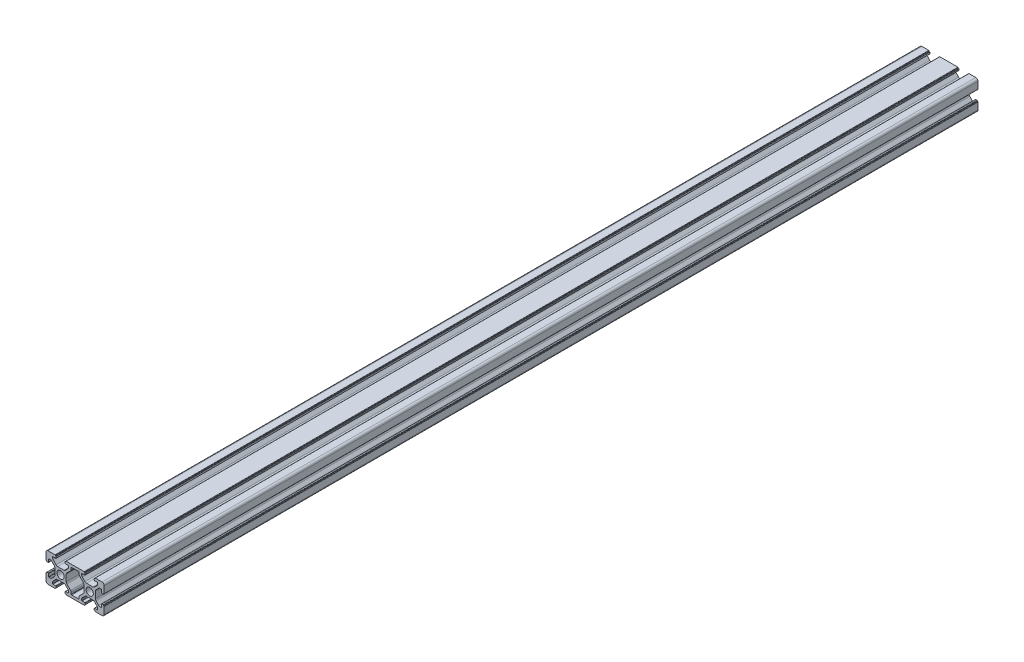
SolidWorks part; units mm, degrees
material "6063-O"
ref_plane "Front Plane" through (0, 0, 0) normal (0, 0, 1) x (1, 0, 0)
ref_plane "Top Plane" through (0, 0, 0) normal (0, 1, 0) x (1, 0, 0)
ref_plane "Right Plane" through (0, 0, 0) normal (1, 0, 0) x (0, 0, -1)
sketch "Sketch1" plane through (0, 0, 0) normal (0, 0, 1) x (1, 0, 0)
  line L0 (1.5, 0) -> (6.2, 0)
  line L1 (40, 1.5) -> (40, 6.2)
  line L2 (38.5, 20) -> (33.8, 20)
  line L3 (0, 18.5) -> (0, 13.8)
  line L4 (17.6, 1.8) -> (22.4, 1.8)
  line L5 (32.218, 13.9) -> (27.782, 13.9)
  line L6 (26.1, 12.218) -> (26.1, 7.782)
  line L7 (17.6, 18.2) -> (22.4, 18.2)
  line L8 (12.218, 13.9) -> (7.9864, 13.9)
  line L9 (6.1, 12.218) -> (6.1, 7.782)
  line L10 (7.782, 6.1) -> (12.218, 6.1)
  line L11 (13.9, 7.782) -> (13.9, 12.218)
  line L12 (27.782, 6.1) -> (32.218, 6.1)
  line L13 (33.9, 7.782) -> (33.9, 12.218)
  line L14 (26.7213, 14.3393) -> (24.9393, 16.1213)
  line L15 (33.2787, 14.3393) -> (35.0607, 16.1213)
  line L16 (34.3393, 13.2787) -> (36.1213, 15.0607)
  line L17 (25.6607, 6.7213) -> (23.1393, 4.2)
  line L18 (15.2, 1.8) -> (13.4, 1.8)
  line L19 (26.7213, 5.6607) -> (24.9393, 3.8787)
  line L20 (24.8, 1.8) -> (26.6, 1.8)
  line L21 (15.3, 18.2) -> (13.1, 18.2)
  line L22 (13.2787, 14.3393) -> (15.1607, 16.2213)
  line L23 (14.3393, 13.2787) -> (16.8607, 15.8)
  line L24 (5.6607, 6.7213) -> (3.8787, 4.9393)
  line L25 (6.7213, 5.6607) -> (4.9393, 3.8787)
  line L26 (6.897, 14.3689) -> (4.9106, 16.4674)
  line L27 (5.6607, 13.2787) -> (3.8787, 15.0607)
  line L28 (14.3393, 6.7213) -> (16.8607, 4.2)
  line L29 (13.2787, 5.6607) -> (15.0607, 3.8787)
  line L30 (24.8, 18.2) -> (26.6, 18.2)
  line L31 (25.6607, 13.2787) -> (23.1393, 15.8)
  line L32 (34.3393, 6.7213) -> (36.1213, 4.9393)
  line L33 (33.2787, 5.6607) -> (35.0607, 3.8787)
  line L34 (1.8, 15.2) -> (1.8, 13.4)
  line L35 (24.5, 2.1) -> (24.5, 2.818)
  line L36 (4.5, 2.1) -> (4.5, 2.818)
  line L37 (2.818, 4.5) -> (2.1, 4.5)
  line L38 (4.5, 17.9) -> (4.5, 17.4986)
  line L39 (2.818, 15.5) -> (2.1, 15.5)
  line L40 (15.6, 17.9) -> (15.6, 17.282)
  line L41 (15.5, 2.818) -> (15.5, 2.1)
  line L42 (38.2, 15.2) -> (38.2, 13.4)
  line L43 (35.5, 2.818) -> (35.5, 2.1)
  line L44 (37.182, 4.5) -> (37.9, 4.5)
  line L45 (35.5, 17.182) -> (35.5, 17.9)
  line L46 (37.182, 15.5) -> (37.9, 15.5)
  line L47 (17.3, 2.1) -> (17.3, 3.1393)
  line L48 (22.7, 2.1) -> (22.7, 3.1393)
  line L49 (17.3, 17.9) -> (17.3, 16.8607)
  line L50 (22.7, 17.9) -> (22.7, 16.8607)
  line L51 (24.5, 17.9) -> (24.5, 17.182)
  line L52 (6.9, 19.3) -> (6.9, 18.2)
  line L53 (13.1, 19.3) -> (13.1, 18.2)
  line L54 (6.9, 1.5) -> (6.9, 0.7)
  line L55 (13.1, 1.5) -> (13.1, 0.7)
  line L56 (13.8, 0) -> (26.2, 0)
  line L57 (6.6, 1.8) -> (4.8, 1.8)
  line L58 (6.9, 18.2) -> (4.8, 18.2)
  line L59 (6.2, 20) -> (1.5, 20)
  line L60 (39.3, 6.9) -> (38.5, 6.9)
  line L61 (39.3, 13.1) -> (38.5, 13.1)
  line L62 (1.5, 13.1) -> (0.7, 13.1)
  line L63 (1.5, 6.9) -> (0.7, 6.9)
  line L64 (0, 6.2) -> (0, 1.5)
  line L65 (1.8, 6.6) -> (1.8, 4.8)
  line L66 (38.2, 6.6) -> (38.2, 4.8)
  line L67 (40, 13.8) -> (40, 18.5)
  line L68 (33.1, 19.3) -> (33.1, 18.5)
  line L69 (26.9, 19.3) -> (26.9, 18.5)
  line L70 (26.9, 1.5) -> (26.9, 0.7)
  line L71 (33.1, 1.5) -> (33.1, 0.7)
  line L72 (33.8, 0) -> (38.5, 0)
  line L73 (33.4, 1.8) -> (35.2, 1.8)
  line L74 (26.2, 20) -> (13.8, 20)
  line L75 (33.4, 18.2) -> (35.2, 18.2)
  line L76 (6.7, 0.5) -> (6.6, 0.5)
  line L77 (6.4, 0.3) -> (6.4, 0.2)
  line L78 (13.3, 0.5) -> (13.4, 0.5)
  line L79 (13.6, 0.3) -> (13.6, 0.2)
  line L80 (26.7, 0.5) -> (26.6, 0.5)
  line L81 (26.4, 0.3) -> (26.4, 0.2)
  line L82 (33.3, 0.5) -> (33.4, 0.5)
  line L83 (33.6, 0.3) -> (33.6, 0.2)
  line L85 (6.4, 19.8) -> (6.4, 19.7)
  line L86 (6.6, 19.5) -> (6.7, 19.5)
  line L87 (13.6, 19.8) -> (13.6, 19.7)
  line L88 (13.4, 19.5) -> (13.3, 19.5)
  line L89 (26.4, 19.8) -> (26.4, 19.7)
  line L90 (26.6, 19.5) -> (26.7, 19.5)
  line L91 (33.6, 19.8) -> (33.6, 19.7)
  line L92 (33.4, 19.5) -> (33.3, 19.5)
  line L93 (0.5, 13.3) -> (0.5, 13.4)
  line L94 (0.3, 13.6) -> (0.2, 13.6)
  line L95 (0.5, 6.7) -> (0.5, 6.6)
  line L96 (0.3, 6.4) -> (0.2, 6.4)
  line L97 (39.5, 13.3) -> (39.5, 13.4)
  line L98 (39.7, 13.6) -> (39.8, 13.6)
  line L99 (39.5, 6.7) -> (39.5, 6.6)
  line L100 (39.7, 6.4) -> (39.8, 6.4)
  circle A0 centre (10, 10) radius 2.5
  circle A1 centre (30, 10) radius 2.5
  arc A2 (38.5, 0) -> (40, 1.5) centre (38.5, 1.5) ccw
  arc A3 (40, 18.5) -> (38.5, 20) centre (38.5, 18.5) ccw
  arc A4 (1.5, 0) -> (0, 1.5) centre (1.5, 1.5) cw
  arc A5 (1.5, 20) -> (0, 18.5) centre (1.5, 18.5) ccw
  arc A6 (26.7213, 5.6607) -> (27.782, 6.1) centre (27.782, 4.6) cw
  arc A7 (32.218, 6.1) -> (33.2787, 5.6607) centre (32.218, 4.6) cw
  arc A8 (33.9, 7.782) -> (34.3393, 6.7213) centre (35.4, 7.782) ccw
  arc A9 (33.2787, 14.3393) -> (32.218, 13.9) centre (32.218, 15.4) cw
  arc A10 (14.3393, 6.7213) -> (13.9, 7.782) centre (15.4, 7.782) cw
  arc A11 (14.3393, 13.2787) -> (13.9, 12.218) centre (15.4, 12.218) ccw
  arc A12 (25.6607, 6.7213) -> (26.1, 7.782) centre (24.6, 7.782) ccw
  arc A13 (26.1, 12.218) -> (25.6607, 13.2787) centre (24.6, 12.218) ccw
  arc A14 (27.782, 13.9) -> (26.7213, 14.3393) centre (27.782, 15.4) cw
  arc A15 (5.6607, 13.2787) -> (6.1, 12.218) centre (4.6, 12.218) cw
  arc A16 (5.6607, 6.7213) -> (6.1, 7.782) centre (4.6, 7.782) ccw
  arc A17 (13.2787, 5.6607) -> (12.218, 6.1) centre (12.218, 4.6) ccw
  arc A18 (6.7213, 5.6607) -> (7.782, 6.1) centre (7.782, 4.6) cw
  arc A19 (13.2787, 14.3393) -> (12.218, 13.9) centre (12.218, 15.4) cw
  arc A20 (6.897, 14.3689) -> (7.9864, 13.9) centre (7.9864, 15.4) ccw
  arc A21 (36.1213, 4.9393) -> (37.182, 4.5) centre (37.182, 6) ccw
  arc A22 (36.1213, 15.0607) -> (37.182, 15.5) centre (37.182, 14) cw
  arc A23 (35.0607, 16.1213) -> (35.5, 17.182) centre (34, 17.182) ccw
  arc A24 (24.5, 17.182) -> (24.9393, 16.1213) centre (26, 17.182) ccw
  arc A25 (22.7, 16.8607) -> (23.1393, 15.8) centre (24.2, 16.8607) ccw
  arc A26 (17.3, 16.8607) -> (16.8607, 15.8) centre (15.8, 16.8607) cw
  arc A27 (4.9106, 16.4674) -> (4.5, 17.4986) centre (6, 17.4986) cw
  arc A28 (15.6, 17.282) -> (15.1607, 16.2213) centre (14.1, 17.282) cw
  arc A29 (3.8787, 15.0607) -> (2.818, 15.5) centre (2.818, 14) ccw
  arc A30 (3.8787, 4.9393) -> (2.818, 4.5) centre (2.818, 6) cw
  arc A31 (4.9393, 3.8787) -> (4.5, 2.818) centre (6, 2.818) ccw
  arc A32 (35.0607, 3.8787) -> (35.5, 2.818) centre (34, 2.818) cw
  arc A33 (24.9393, 3.8787) -> (24.5, 2.818) centre (26, 2.818) ccw
  arc A34 (22.7, 3.1393) -> (23.1393, 4.2) centre (24.2, 3.1393) cw
  arc A35 (17.3, 3.1393) -> (16.8607, 4.2) centre (15.8, 3.1393) ccw
  arc A36 (15.5, 2.818) -> (15.0607, 3.8787) centre (14, 2.818) ccw
  arc A37 (1.8, 6.6) -> (1.5, 6.9) centre (1.5, 6.6) ccw
  arc A38 (1.8, 13.4) -> (1.5, 13.1) centre (1.5, 13.4) cw
  arc A39 (17.6, 18.2) -> (17.3, 17.9) centre (17.6, 17.9) ccw
  arc A40 (22.4, 1.8) -> (22.7, 2.1) centre (22.4, 2.1) ccw
  arc A41 (17.6, 1.8) -> (17.3, 2.1) centre (17.6, 2.1) cw
  arc A42 (15.2, 1.8) -> (15.5, 2.1) centre (15.2, 2.1) ccw
  arc A43 (6.6, 1.8) -> (6.9, 1.5) centre (6.6, 1.5) cw
  arc A44 (13.4, 1.8) -> (13.1, 1.5) centre (13.4, 1.5) ccw
  arc A45 (24.8, 1.8) -> (24.5, 2.1) centre (24.8, 2.1) cw
  arc A46 (35.2, 1.8) -> (35.5, 2.1) centre (35.2, 2.1) ccw
  arc A47 (26.6, 1.8) -> (26.9, 1.5) centre (26.6, 1.5) cw
  arc A48 (33.4, 1.8) -> (33.1, 1.5) centre (33.4, 1.5) ccw
  arc A49 (26.9, 18.5) -> (26.6, 18.2) centre (26.6, 18.5) cw
  arc A50 (33.1, 18.5) -> (33.4, 18.2) centre (33.4, 18.5) ccw
  arc A51 (37.9, 4.5) -> (38.2, 4.8) centre (37.9, 4.8) ccw
  arc A52 (38.5, 13.1) -> (38.2, 13.4) centre (38.5, 13.4) cw
  arc A53 (38.5, 6.9) -> (38.2, 6.6) centre (38.5, 6.6) ccw
  arc A54 (38.2, 15.2) -> (37.9, 15.5) centre (37.9, 15.2) ccw
  arc A55 (35.2, 18.2) -> (35.5, 17.9) centre (35.2, 17.9) cw
  arc A56 (24.8, 18.2) -> (24.5, 17.9) centre (24.8, 17.9) ccw
  arc A57 (22.4, 18.2) -> (22.7, 17.9) centre (22.4, 17.9) cw
  arc A58 (15.3, 18.2) -> (15.6, 17.9) centre (15.3, 17.9) cw
  arc A59 (4.5, 17.9) -> (4.8, 18.2) centre (4.8, 17.9) cw
  arc A60 (1.8, 15.2) -> (2.1, 15.5) centre (2.1, 15.2) cw
  arc A61 (1.8, 4.8) -> (2.1, 4.5) centre (2.1, 4.8) ccw
  arc A62 (4.5, 2.1) -> (4.8, 1.8) centre (4.8, 2.1) ccw
  arc A63 (34.3393, 13.2787) -> (33.9, 12.218) centre (35.4, 12.218) ccw
  arc A64 (6.4, 0.2) -> (6.2, 0) centre (6.2, 0.2) cw
  arc A65 (6.6, 0.5) -> (6.4, 0.3) centre (6.6, 0.3) ccw
  arc A66 (6.7, 0.5) -> (6.9, 0.7) centre (6.7, 0.7) ccw
  arc A67 (13.6, 0.2) -> (13.8, 0) centre (13.8, 0.2) ccw
  arc A68 (13.4, 0.5) -> (13.6, 0.3) centre (13.4, 0.3) cw
  arc A69 (13.3, 0.5) -> (13.1, 0.7) centre (13.3, 0.7) cw
  arc A70 (26.4, 0.2) -> (26.2, 0) centre (26.2, 0.2) cw
  arc A71 (26.6, 0.5) -> (26.4, 0.3) centre (26.6, 0.3) ccw
  arc A72 (26.7, 0.5) -> (26.9, 0.7) centre (26.7, 0.7) ccw
  arc A73 (33.6, 0.2) -> (33.8, 0) centre (33.8, 0.2) ccw
  arc A74 (33.4, 0.5) -> (33.6, 0.3) centre (33.4, 0.3) cw
  arc A75 (33.3, 0.5) -> (33.1, 0.7) centre (33.3, 0.7) cw
  arc A76 (39.8, 6.4) -> (40, 6.2) centre (39.8, 6.2) cw
  arc A77 (39.5, 6.6) -> (39.7, 6.4) centre (39.7, 6.6) ccw
  arc A78 (39.5, 6.7) -> (39.3, 6.9) centre (39.3, 6.7) ccw
  arc A79 (39.5, 13.3) -> (39.3, 13.1) centre (39.3, 13.3) cw
  arc A80 (39.5, 13.4) -> (39.7, 13.6) centre (39.7, 13.4) cw
  arc A81 (39.8, 13.6) -> (40, 13.8) centre (39.8, 13.8) ccw
  arc A82 (33.3, 19.5) -> (33.1, 19.3) centre (33.3, 19.3) ccw
  arc A83 (33.6, 19.7) -> (33.4, 19.5) centre (33.4, 19.7) cw
  arc A84 (33.6, 19.8) -> (33.8, 20) centre (33.8, 19.8) cw
  arc A85 (26.7, 19.5) -> (26.9, 19.3) centre (26.7, 19.3) cw
  arc A86 (26.4, 19.7) -> (26.6, 19.5) centre (26.6, 19.7) ccw
  arc A87 (26.4, 19.8) -> (26.2, 20) centre (26.2, 19.8) ccw
  arc A88 (0.2, 6.4) -> (0, 6.2) centre (0.2, 6.2) ccw
  arc A89 (0.5, 6.6) -> (0.3, 6.4) centre (0.3, 6.6) cw
  arc A90 (0.5, 6.7) -> (0.7, 6.9) centre (0.7, 6.7) cw
  arc A91 (13.3, 19.5) -> (13.1, 19.3) centre (13.3, 19.3) ccw
  arc A92 (13.6, 19.7) -> (13.4, 19.5) centre (13.4, 19.7) cw
  arc A93 (13.6, 19.8) -> (13.8, 20) centre (13.8, 19.8) cw
  arc A94 (6.2, 20) -> (6.4, 19.8) centre (6.2, 19.8) cw
  arc A95 (6.7, 19.5) -> (6.9, 19.3) centre (6.7, 19.3) cw
  arc A96 (6.4, 19.7) -> (6.6, 19.5) centre (6.6, 19.7) ccw
  arc A97 (0.5, 13.3) -> (0.7, 13.1) centre (0.7, 13.3) ccw
  arc A98 (0.2, 13.6) -> (0, 13.8) centre (0.2, 13.8) cw
  arc A99 (0.5, 13.4) -> (0.3, 13.6) centre (0.3, 13.4) ccw
  point P87 (0, 0)
  point P178 (1.8, 6.9)
  point P181 (1.8, 13.1)
  point P186 (22.7, 1.8)
  point P193 (6.9, 1.8)
  point P204 (33.1, 1.8)
  point P209 (33.1, 18.2)
  point P216 (38.2, 6.9)
  point P243 (6.9, 0.5)
  point P248 (13.6, 0.5)
  point P257 (26.9, 0.5)
extrude "Boss-Extrude2" add sketch "Sketch1" along normal blind 600 contours A57 L7 A39 L49 A26 L23 A11 L11 A10 L28 A35 L47 A41 L4 A40 L48 A34 L17 A12 L6 A13 L31 A25 L50 | A0 | A1 | L59 A5 L3 A98 L94 A99 L93 A97 L62 A38 L34 A60 L39 A29 L27 A15 L9 A16 L24 A30 L37 A61 L65 A37 L63 A90 L95 A89 L96 A88 L64 A4 L0 A64 L77 A65 L76 A66 L54 A43 L57 A62 L36 A31 L25 A18 L10 A17 L29 A36 L41 A42 L18 A44 L55 A69 L78 A68 L79 A67 L56 A70 L81 A71 L80 A72 L70 A47 L20 A45 L35 A33 L19 A6 L12 A7 L33 A32 L43 A46 L73 A48 L71 A75 L82 A74 L83 A73 L72 A2 L1 A76 L100 A77 L99 A78 L60 A53 L66 A51 L44 A21 L32 A8 L13 A63 L16 A22 L46 A54 L42 A52 L61 A79 L97 A80 L98 A81 L67 A3 L2 A84 L91 A83 L92 A82 L68 A50 L75 A55 L45 A23 L15 A9 L5 A14 L14 A24 L51 A56 L30 A49 L69 A85 L90 A86 L89 A87 L74 A93 L87 A92 L88 A91 L53 L21 A58 L40 A28 L22 A19 L8 A20 L26 A27 L38 A59 L58 L52 A95 L86 A96 L85 A94
